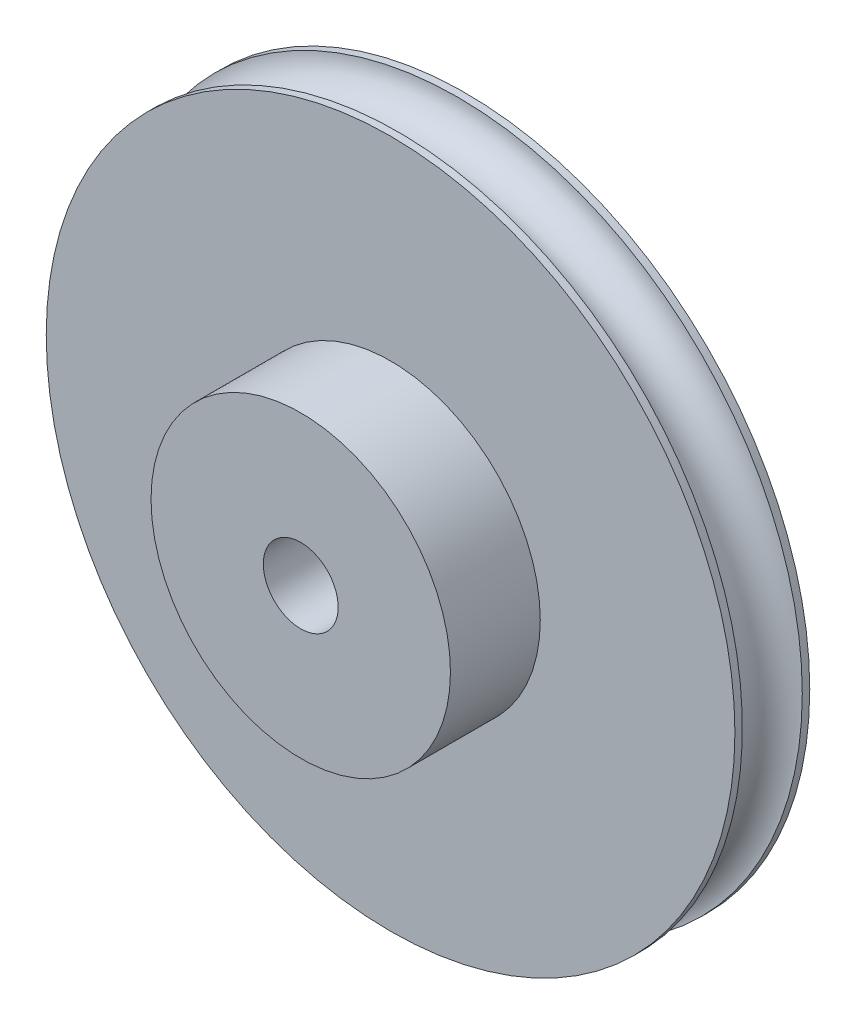
SolidWorks part; units mm, degrees
ref_plane "Plan de face" through (0, 0, 0) normal (0, 0, 1) x (1, 0, 0)
ref_plane "Plan de dessus" through (0, 0, 0) normal (0, 1, 0) x (1, 0, 0)
ref_plane "Plan de droite" through (0, 0, 0) normal (1, 0, 0) x (0, 0, -1)
sketch "Esquisse1" plane through (0, 0, 0) normal (0, 0, 1) x (1, 0, 0)
  circle A0 centre (0, 0) radius 23
  dimension "D1" = 46
extrude "Boss.-Extru.1" add sketch "Esquisse1" along normal blind 5
sketch "Esquisse2" plane through (0, 0, 5) normal (0, 0, 1) x (1, 0, 0)
  circle A0 centre (0, 0) radius 10
  dimension "D1" = 20
extrude "Boss.-Extru.2" add sketch "Esquisse2" along normal blind 6
sketch "Esquisse3" plane through (0, 0, 11) normal (0, 0, 1) x (1, 0, 0)
  circle A0 centre (0, 0) radius 2.5
  dimension "D1" = 5
extrude "Enlèv. mat.-Extru.1" cut sketch "Esquisse3" against normal through all
sketch "Esquisse4" plane through (0, 0, 0) normal (1, 0, 0) x (0, 0, -1)
  line L0 (-2.5, 23) -> (-2.5, 8.0945) construction
  line L1 (0, 23) -> (-5, 23) construction
  line L2 (0, 0) -> (-21.8888, 0) construction
  circle A0 centre (-2.5, 23) radius 2
  dimension "D2" = 4
  dimension "D1" = 23
revolve "Enlèvement de matière-Révolution1" cut sketch "Esquisse4" angle 360 about L2
